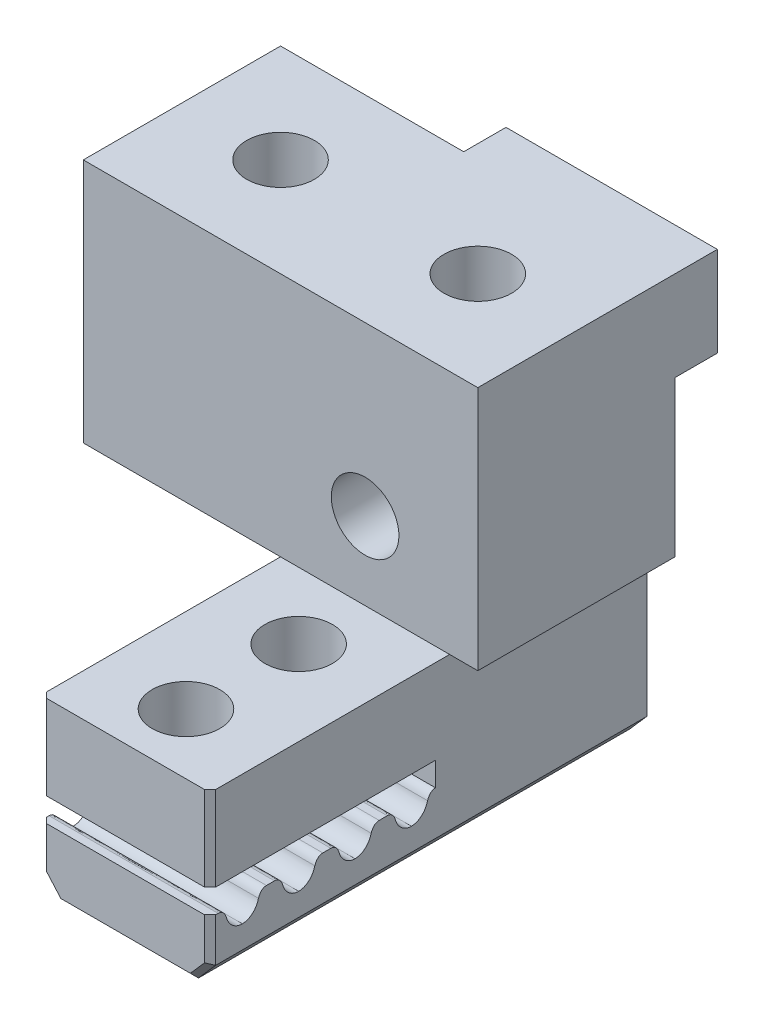
SolidWorks part; units mm, degrees
ref_plane "Front Plane" through (0, 0, 0) normal (0, 0, 1) x (1, 0, 0)
ref_plane "Top Plane" through (0, 0, 0) normal (0, 1, 0) x (1, 0, 0)
ref_plane "Right Plane" through (0, 0, 0) normal (1, 0, 0) x (0, 0, -1)
sketch "Sketch1" plane through (0, 0, 0) normal (0, 0, 1) x (1, 0, 0)
  line L0 (3, 3.05) -> (3, -2.2538)
  line L1 (-3, 3.05) -> (-3, -2.2538)
  line L7 (-3, 3.05) -> (3, 3.05)
  line L13 (-3, -2.2538) -> (-2.3882, -2.95)
  line L14 (3, -2.2538) -> (2.3882, -2.95)
  line L16 (-2.3882, -2.95) -> (2.3882, -2.95)
extrude "Boss-Extrude1" add sketch "Sketch1" along normal blind 13
sketch "Sketch6" plane through (0, 3.05, 0) normal (0, 1, 0) x (1, 0, 0)
  line L0 (-3, -5) -> (-3, 0)
  line L1 (-3, 0) -> (3, 0)
  line L3 (-3, -5) -> (3, -5)
  line L6 (3, -5) -> (3, 0)
  line L7 (3, 0) -> (-3, 0) construction
extrude "Boss-Extrude4" add sketch "Sketch6" along normal blind 5.6
sketch "Sketch16" plane through (0, 3.05, 0) normal (0, 1, 0) x (1, 0, 0)
  line L4 (3, -5) -> (-3, -5)
  line L5 (-3, -5) -> (-3, -13)
  line L6 (-3, -13) -> (3, -13)
  line L7 (3, -13) -> (3, -5)
  line L8 (3, -5) -> (-3, -5)
  line L9 (-3, -5) -> (-3, -13)
  line L10 (-3, -13) -> (3, -13)
  line L11 (3, -13) -> (3, -5)
  dimension "D1" = 0
extrude "Boss-Extrude5" add sketch "Sketch16" along normal blind 0.1
sketch "Sketch18" plane through (0, 0, 0) normal (1, 0, 0) x (0, 0, -1)
  line L0 (-8.8572, -0.0702) -> (-12.8572, -0.0702)
  line L2 (-12.8572, -0.7) -> (-12.7144, -0.7)
  line L3 (-11, -0.7) -> (-10.8572, -0.7)
  line L4 (-10.8572, -0.7) -> (-10.7144, -0.7)
  line L5 (-9, -0.7) -> (-8.8572, -0.7)
  line L6 (-8.8572, -0.7) -> (-8.7144, -0.7)
  line L7 (-7, -0.7) -> (-6.8572, -0.7)
  line L8 (-6.8572, -0.7) -> (-6.7144, -0.7)
  line L9 (-5, -0.0702) -> (-5, -0.7)
  line L11 (-5, -0.0702) -> (-8.8572, -0.0702)
  line L12 (-13, -2.95) -> (0, -2.95) construction
  line L13 (-5.8572, -1.45) -> (-5, -1.45) construction
  line L14 (-5, -1.45) -> (-11.8572, -1.45) construction
  line L15 (-5, 3.15) -> (-5, -1.45) construction
  line L16 (-5, -0.7) -> (-5, -1.45) construction
  line L17 (-12.8572, -0.0702) -> (-13, -0.0702)
  line L20 (-13, -0.0702) -> (-13, -0.7)
  line L22 (-12.8572, -0.7) -> (-13, -0.7)
  spline S0 degree 2 poles (-12.7144, -0.7) (-12.5198, -0.7) (-12.43, -0.9509) knots 0.103448 0.103448 0.103448 0.137931 0.137931 0.137931
  spline S1 degree 3 poles (-12.43, -0.9509) (-12.3594, -1.2388) (-12.13, -1.45) (-11.8572, -1.45) knots 0.137931 0.137931 0.137931 0.137931 0.172414 0.172414 0.172414 0.172414
  spline S2 degree 3 poles (-11.8572, -1.45) (-11.5844, -1.45) (-11.355, -1.2388) (-11.2844, -0.9509) knots 0.172414 0.172414 0.172414 0.172414 0.206897 0.206897 0.206897 0.206897
  spline S3 degree 2 poles (-11.2844, -0.9509) (-11.1946, -0.7) (-11, -0.7) knots 0.206897 0.206897 0.206897 0.241379 0.241379 0.241379
  spline S4 degree 2 poles (-10.7144, -0.7) (-10.5198, -0.7) (-10.43, -0.9509) knots 0.310345 0.310345 0.310345 0.344828 0.344828 0.344828
  spline S5 degree 3 poles (-10.43, -0.9509) (-10.3594, -1.2388) (-10.13, -1.45) (-9.8572, -1.45) knots 0.344828 0.344828 0.344828 0.344828 0.37931 0.37931 0.37931 0.37931
  spline S6 degree 3 poles (-9.8572, -1.45) (-9.5844, -1.45) (-9.355, -1.2388) (-9.2844, -0.9509) knots 0.37931 0.37931 0.37931 0.37931 0.413793 0.413793 0.413793 0.413793
  spline S7 degree 2 poles (-9.2844, -0.9509) (-9.1946, -0.7) (-9, -0.7) knots 0.413793 0.413793 0.413793 0.448276 0.448276 0.448276
  spline S8 degree 2 poles (-8.7144, -0.7) (-8.5198, -0.7) (-8.43, -0.9509) knots 0.517241 0.517241 0.517241 0.551724 0.551724 0.551724
  spline S9 degree 3 poles (-8.43, -0.9509) (-8.3594, -1.2388) (-8.13, -1.45) (-7.8572, -1.45) knots 0.551724 0.551724 0.551724 0.551724 0.586207 0.586207 0.586207 0.586207
  spline S10 degree 3 poles (-7.8572, -1.45) (-7.5844, -1.45) (-7.355, -1.2388) (-7.2844, -0.9509) knots 0.586207 0.586207 0.586207 0.586207 0.62069 0.62069 0.62069 0.62069
  spline S11 degree 2 poles (-7.2844, -0.9509) (-7.1946, -0.7) (-7, -0.7) knots 0.62069 0.62069 0.62069 0.655172 0.655172 0.655172
  spline S12 degree 2 poles (-6.7144, -0.7) (-6.5198, -0.7) (-6.43, -0.9509) knots 0.724138 0.724138 0.724138 0.758621 0.758621 0.758621
  spline S13 degree 3 poles (-6.43, -0.9509) (-6.3594, -1.2388) (-6.13, -1.45) (-5.8572, -1.45) knots 0.758621 0.758621 0.758621 0.758621 0.793103 0.793103 0.793103 0.793103
  spline S14 degree 3 poles (-5.8572, -1.45) (-5.5844, -1.45) (-5.355, -1.2388) (-5.2844, -0.9509) knots 0.793103 0.793103 0.793103 0.793103 0.827586 0.827586 0.827586 0.827586
  spline S15 degree 2 poles (-5.2844, -0.9509) (-5.1946, -0.7) (-5, -0.7) knots 0.827586 0.827586 0.827586 0.862069 0.862069 0.862069
  dimension "D1" = 1.5
  dimension "D2" = 1.3798
extrude "Cut-Extrude6" cut sketch "Sketch18" against normal blind 3.6 and the other way blind 4
sketch "Sketch15" plane through (0, 8.65, 0) normal (0, 1, 0) x (1, 0, 0)
  line L0 (0, -13) -> (0, -5) construction
  line L1 (-3, -13) -> (3, -13) construction
  line L2 (-3, -5) -> (3, -5) construction
  line L3 (2.008, -10.7144) -> (2.008, -11) construction
  line L4 (3, -10.7144) -> (-3, -10.7144) construction
  line L5 (3, -11) -> (-3, -11) construction
  line L6 (2.008, -10.8572) -> (0, -10.8572) construction
  line L7 (1.0382, -6.7144) -> (1.0382, -7) construction
  line L8 (3, -6.7144) -> (-3, -6.7144) construction
  line L9 (3, -7) -> (-3, -7) construction
  line L10 (1.0382, -6.8572) -> (0, -6.8572) construction
  circle A0 centre (0, -6.8572) radius 1.5 construction
  circle A1 centre (0, -10.8572) radius 1.5 construction
  circle A2 centre (0, -10.8572) radius 1.2
  circle A4 centre (0, -6.8572) radius 1.2
extrude "Cut-Extrude7" cut sketch "Sketch15" against normal up to surface (8.7202 mm away) up to face at (0, -0.0702, 9)
sketch "Sketch19" plane through (0, -0.0702, 0) normal (0, -1, 0) x (1, 0, 0)
  line L4 (-3, 13) -> (-3, 5)
  line L5 (-3, 5) -> (3, 5)
  line L6 (3, 5) -> (3, 13)
  line L7 (3, 13) -> (-3, 13)
  line L8 (-3, 13) -> (-3, 5)
  line L9 (-3, 5) -> (3, 5)
  line L10 (3, 5) -> (3, 13)
  line L11 (3, 13) -> (-3, 13)
  circle A0 centre (0, 10.8572) radius 1.2 construction
  circle A1 centre (0, 6.8572) radius 1.2 construction
  circle A2 centre (0, 10.8572) radius 1.2
  circle A3 centre (0, 6.8572) radius 1.2
  dimension "D1" = 0
extrude "Cut-Extrude8" cut sketch "Sketch19" against normal blind 0.2202
sketch "Sketch12" plane through (0, 0, 5) normal (0, 0, 1) x (1, 0, 0)
  circle A0 centre (0, 5.85) radius 1.5 construction
  circle A1 centre (0, 5.85) radius 1.2
extrude "Cut-Extrude5" cut sketch "Sketch12" against normal blind 6
chamfer "Chamfer1" distance 0.2 angle 45 7 edges at (-3, 1.65, 13) (-3, -1.4769, 13) (-2.6941, -2.6019, 13) (0, -2.95, 13) (2.6941, -2.6019, 13) (3, -1.4769, 13) (3, 1.65, 13)
sketch "Sketch21" plane through (0, 0, 0) normal (0, 0, -1) x (-1, 0, 0)
  line L10 (-2.3882, -2.95) -> (2.3882, -2.95)
  line L11 (2.3882, -2.95) -> (3, -2.2538)
  line L12 (3, -2.2538) -> (3, 8.65)
  line L13 (3, 8.65) -> (-3, 8.65)
  line L14 (-3, 8.65) -> (-3, -2.2538)
  line L15 (-3, -2.2538) -> (-2.3882, -2.95)
  line L19 (-2.3882, -2.95) -> (2.3882, -2.95)
  line L20 (2.3882, -2.95) -> (3, -2.2538)
  line L21 (3, -2.2538) -> (3, 8.65)
  line L22 (3, 8.65) -> (-3, 8.65)
  line L23 (-3, 8.65) -> (-3, -2.2538)
  line L24 (-3, -2.2538) -> (-2.3882, -2.95)
  circle A0 centre (0, 5.85) radius 1.2 construction
  circle A1 centre (0, 5.85) radius 1.2
  dimension "D1" = 0
extrude "Boss-Extrude6" add sketch "Sketch21" along normal blind 2.5
sketch "Sketch24" plane through (0, 0, 5) normal (0, 0, 1) x (1, 0, 0)
  line L4 (-3, 8.65) -> (-3, 3.15)
  line L5 (-3, 3.15) -> (3, 3.15)
  line L6 (3, 3.15) -> (3, 8.65)
  line L7 (3, 8.65) -> (-3, 8.65)
  line L8 (-3, 8.65) -> (-3, 3.15)
  line L9 (-3, 3.15) -> (3, 3.15)
  line L10 (3, 3.15) -> (3, 8.65)
  line L11 (3, 8.65) -> (-3, 8.65)
  dimension "D1" = 0
extrude "Cut-Extrude10" cut sketch "Sketch24" against normal blind 8.5
sketch "Sketch25" plane through (0, 3.15, 0) normal (0, 1, 0) x (1, 0, 0)
  line L0 (3, -12.8) -> (3, 2.5) construction
  line L2 (-3, 2.5) -> (3, 2.5)
  line L3 (-3, 2.5) -> (-3, -4.5)
  line L4 (-3, -4.5) -> (3, -4.5)
  line L5 (3, 2.5) -> (3, -4.5)
  dimension "D1" = 7
extrude "Boss-Extrude8" add sketch "Sketch25" along normal blind 12.9
sketch "Sketch26" plane through (0, 0, -2.5) normal (0, 0, -1) x (-1, 0, 0)
  line L0 (3, -2.2538) -> (3, 16.05) construction
  line L1 (-3, 16.05) -> (3, 16.05)
  line L2 (-3, 16.05) -> (-3, 8.66)
  line L3 (-3, 8.66) -> (3, 8.66)
  line L4 (3, 16.05) -> (3, 8.66)
extrude "Boss-Extrude9" add sketch "Sketch26" along normal blind 3
sketch "Sketch30" plane through (0, 0, -2.5) normal (0, 0, -1) x (-1, 0, 0)
  circle A2 centre (0, 5.9) radius 1.2
extrude "Cut-Extrude13" cut sketch "Sketch30" against normal blind 8
sketch "Sketch31" plane through (3, 0, 0) normal (1, 0, 0) x (0, 0, -1)
  line L1 (-4.5, 12.15) -> (2.5, 12.15)
  line L2 (-4.5, 12.15) -> (-4.5, 3.15)
  line L3 (-4.5, 3.15) -> (2.5, 3.15)
  line L4 (2.5, 12.15) -> (2.5, 3.15)
  line L5 (-12.8, 3.15) -> (-4.5, 3.15) construction
extrude "Boss-Extrude11" add sketch "Sketch31" along normal blind 1
sketch "Sketch32" plane through (-3, 0, 0) normal (-1, 0, 0) x (0, 0, 1)
  line L0 (-2.5, -2.2538) -> (-2.5, 8.66) construction
  line L1 (4.5, 12.15) -> (-2.5, 12.15)
  line L2 (4.5, 12.15) -> (4.5, 3.15)
  line L3 (4.5, 3.15) -> (-2.5, 3.15)
  line L4 (-2.5, 12.15) -> (-2.5, 3.15)
  line L6 (4.5, 3.15) -> (12.8, 3.15) construction
extrude "Boss-Extrude12" add sketch "Sketch32" along normal blind 1
sketch "Sketch33" plane through (3, 0, 0) normal (1, 0, 0) x (0, 0, -1)
  line L6 (2.5, 12.15) -> (2.5, 8.66)
  line L7 (2.5, 8.66) -> (5.5, 8.66)
  line L8 (5.5, 8.66) -> (5.5, 16.05)
  line L9 (5.5, 16.05) -> (-4.5, 16.05)
  line L10 (-4.5, 16.05) -> (-4.5, 12.15)
  line L11 (-4.5, 12.15) -> (2.5, 12.15)
  line L12 (2.5, 12.15) -> (2.5, 8.66)
  line L13 (2.5, 8.66) -> (5.5, 8.66)
  line L14 (5.5, 8.66) -> (5.5, 16.05)
  line L15 (5.5, 16.05) -> (-4.5, 16.05)
  line L16 (-4.5, 16.05) -> (-4.5, 12.15)
  line L17 (-4.5, 12.15) -> (2.5, 12.15)
  dimension "D1" = 0
extrude "Boss-Extrude13" add sketch "Sketch33" along normal up to surface (1 mm away) up to face at (4, 7.65, 1)
sketch "Sketch34" plane through (-3, 0, 0) normal (-1, 0, 0) x (0, 0, 1)
  line L6 (-2.5, 12.15) -> (4.5, 12.15)
  line L7 (4.5, 12.15) -> (4.5, 16.05)
  line L8 (4.5, 16.05) -> (-5.5, 16.05)
  line L9 (-5.5, 16.05) -> (-5.5, 8.66)
  line L10 (-5.5, 8.66) -> (-2.5, 8.66)
  line L11 (-2.5, 8.66) -> (-2.5, 12.15)
  line L12 (-2.5, 12.15) -> (4.5, 12.15)
  line L13 (4.5, 12.15) -> (4.5, 16.05)
  line L14 (4.5, 16.05) -> (-5.5, 16.05)
  line L15 (-5.5, 16.05) -> (-5.5, 8.66)
  line L16 (-5.5, 8.66) -> (-2.5, 8.66)
  line L17 (-2.5, 8.66) -> (-2.5, 12.15)
  dimension "D1" = 0
extrude "Boss-Extrude14" add sketch "Sketch34" along normal up to surface (1 mm away) up to face at (-4, 7.65, 1)
sketch "Sketch35" plane through (-4, 0, 0) normal (-1, 0, 0) x (0, 0, 1)
  line L0 (4.5, 3.15) -> (4.5, 16.05) construction
  line L1 (-5.5, 16.05) -> (4.5, 16.05)
  line L2 (-5.5, 16.05) -> (-5.5, 11.85)
  line L3 (-5.5, 11.85) -> (4.5, 11.85)
  line L4 (4.5, 16.05) -> (4.5, 11.85)
  dimension "D1" = 4.2
extrude "Cut-Extrude14" cut sketch "Sketch35" against normal blind 10
sketch "Sketch36" plane through (-4, 0, 0) normal (-1, 0, 0) x (0, 0, 1)
  line L6 (4.5, 3.15) -> (4.5, 11.85)
  line L7 (4.5, 11.85) -> (-5.5, 11.85)
  line L8 (-5.5, 11.85) -> (-5.5, 8.66)
  line L9 (-5.5, 8.66) -> (-2.5, 8.66)
  line L10 (-2.5, 8.66) -> (-2.5, 3.15)
  line L11 (-2.5, 3.15) -> (4.5, 3.15)
  line L12 (4.5, 3.15) -> (4.5, 11.85)
  line L13 (4.5, 11.85) -> (-5.5, 11.85)
  line L14 (-5.5, 11.85) -> (-5.5, 8.66)
  line L15 (-5.5, 8.66) -> (-2.5, 8.66)
  line L16 (-2.5, 8.66) -> (-2.5, 3.15)
  line L17 (-2.5, 3.15) -> (4.5, 3.15)
  dimension "D1" = 0
extrude "Boss-Extrude15" add sketch "Sketch36" along normal blind 6
sketch "Sketch38" plane through (0, 11.85, 0) normal (0, 1, 0) x (1, 0, 0)
  line L0 (-3, 5.5) -> (-3, -4.5) construction
  line L1 (4, 5.5) -> (-10, 5.5) construction
  line L2 (4, -4.5) -> (-10, -4.5) construction
  line L3 (-3, 2.5) -> (-10, -4.5) construction
  line L5 (0, -13) -> (0, 5.5) construction
  line L6 (-2.8, -13) -> (2.8, -13) construction
  line L7 (4, 2.5) -> (-10, 2.5) construction
  line L8 (4, 2.5) -> (-3, -4.5) construction
  line L9 (-3, 2.5) -> (4, -4.5) construction
  circle A0 centre (-6.5, -1) radius 1.2 construction
  circle A1 centre (0.5, -1) radius 1.2
  dimension "D1" = 2.4
extrude "Cut-Extrude15" cut sketch "Sketch38" against normal blind 4
sketch "Sketch39" plane through (0, 11.85, 0) normal (0, 1, 0) x (1, 0, 0)
  circle A0 centre (-6.5, -1) radius 1.2
extrude "Cut-Extrude16" cut sketch "Sketch39" against normal blind 10
sketch "Sketch40" plane through (0, 11.85, 0) normal (0, 1, 0) x (1, 0, 0)
  line L1 (4, 4) -> (-10, 4)
  line L2 (-10, 4) -> (-10, 5.5)
  line L4 (-10, 5.5) -> (4, 5.5)
  line L5 (4, 5.5) -> (4, 4)
extrude "Cut-Extrude17" cut sketch "Sketch40" against normal blind 10
sketch "Sketch41" plane through (0, 0, -4) normal (0, 0, -1) x (-1, 0, 0)
  line L0 (-4, 8.66) -> (10, 8.66) construction
  line L1 (10, 11.85) -> (3.5, 11.85)
  line L2 (10, 11.85) -> (10, 8.66)
  line L3 (10, 8.66) -> (3.5, 8.66)
  line L4 (3.5, 11.85) -> (3.5, 8.66)
extrude "Cut-Extrude18" cut sketch "Sketch41" against normal up to surface (1.5 mm away) up to face at (-1.2, 5.9, -2.5)
